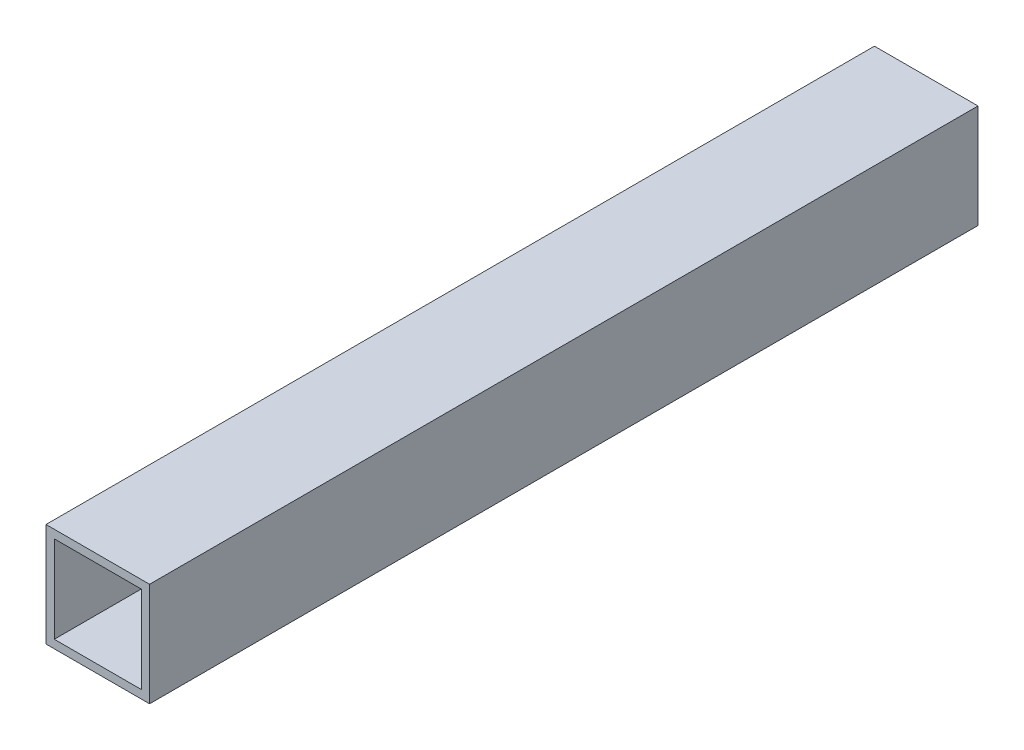
SolidWorks part; units mm, degrees
ref_plane "Front Plane" through (0, 0, 0) normal (0, 0, 1) x (1, 0, 0)
ref_plane "Top Plane" through (0, 0, 0) normal (0, 1, 0) x (1, 0, 0)
ref_plane "Right Plane" through (0, 0, 0) normal (1, 0, 0) x (0, 0, -1)
sketch "Sketch1" plane through (0, 0, 0) normal (0, 0, 1) x (1, 0, 0)
  line L1 (-12.5, -12.5) -> (12.5, -12.5)
  line L2 (-12.5, -12.5) -> (-12.5, 12.5)
  line L3 (-12.5, 12.5) -> (12.5, 12.5)
  line L4 (12.5, -12.5) -> (12.5, 12.5)
  line L5 (-12.5, -12.5) -> (12.5, 12.5) construction
  line L6 (-12.5, 12.5) -> (12.5, -12.5) construction
  line L7 (-10.5, 10.5) -> (10.5, 10.5)
  line L8 (-10.5, 10.5) -> (-10.5, -10.5)
  line L9 (-10.5, -10.5) -> (10.5, -10.5)
  line L10 (10.5, 10.5) -> (10.5, -10.5)
  line L11 (-10.5, 10.5) -> (10.5, -10.5) construction
  line L12 (-10.5, -10.5) -> (10.5, 10.5) construction
  point P0 (0, 0)
  point P6 (0, 0)
  dimension "D1" = 25
  dimension "D2" = 25
  dimension "D3" = 2
extrude "Boss-Extrude1" add sketch "Sketch1" along normal blind 200
